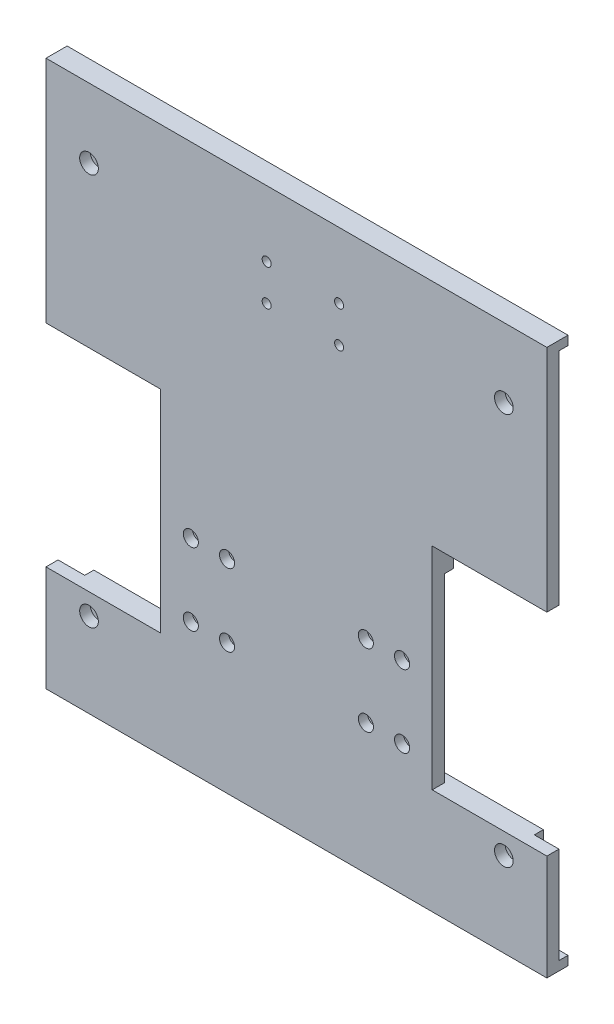
SolidWorks part; units mm, degrees
material "純碳鋼"
ref_plane "前基準面" through (0, 0, 0) normal (0, 0, 1) x (1, 0, 0)
ref_plane "上基準面" through (0, 0, 0) normal (0, 1, 0) x (1, 0, 0)
ref_plane "右基準面" through (0, 0, 0) normal (1, 0, 0) x (0, 0, -1)
sketch "草圖1" plane through (0, 0, 0) normal (0, 0, 1) x (1, 0, 0)
  line L1 (75, -80) -> (-75, -80)
  line L2 (75, -80) -> (75, 80)
  line L3 (75, 80) -> (-75, 80)
  line L4 (-75, -80) -> (-75, 80)
  line L5 (75, -80) -> (-75, 80) construction
  line L6 (75, 80) -> (-75, -80) construction
  point P0 (0, 0)
  dimension "D1" = 150
  dimension "D2" = 160
extrude "填料-伸長1" add sketch "草圖1" along normal blind 7
sketch "草圖2" plane through (0, 0, 0) normal (0, 0, -1) x (-1, 0, 0)
  line L0 (-45, 80) -> (-45, -80)
  line L1 (-75, 80) -> (75, 80) construction
  line L2 (75, -80) -> (-75, -80) construction
  line L3 (45, 80) -> (45, -80)
  line L4 (-75, -80) -> (-75, 80) construction
  line L6 (-45, 35) -> (45, 35)
  line L7 (-75, 12) -> (-45, 12)
  line L8 (-45, 12) -> (-45, -58)
  line L9 (-45, -58) -> (-75, -58)
  line L10 (-75, -58) -> (-75, 12)
  line L11 (45, 12) -> (75, 12)
  line L12 (75, 80) -> (75, -80) construction
  line L13 (75, 12) -> (75, -58)
  line L14 (75, -58) -> (45, -58)
  line L15 (45, -58) -> (45, 12)
  dimension "D1" = 90
  dimension "D2" = 30
  dimension "D3" = 45
  dimension "D4" = 70
  dimension "D5" = 70
  dimension "D6" = 22
extrude "除料-伸長1" cut sketch "草圖2" against normal blind 10 contours L13 L14 L15 L11 | L10 L7 L8 L9
sketch "草圖3" plane through (0, 0, 0) normal (0, 0, -1) x (-1, 0, 0)
  line L0 (-45, -58) -> (45, -58)
  line L1 (-45, 12) -> (-45, -58) construction
  line L2 (-45, -57) -> (-11, -57)
  line L3 (-11, -57) -> (-11, -10.5)
  line L4 (-11, -10.5) -> (-45, -10.5)
  circle A0 centre (-35, -25.75) radius 1.5
  circle A1 centre (-23, -25.75) radius 1.5
  circle A2 centre (-35.025, -49.75) radius 1.5
  circle A3 centre (-23.025, -49.75) radius 1.5
  dimension "D3" = 10
  dimension "D5" = 12
  dimension "D7" = 24
  dimension "D9" = 12
  dimension "D1" = 34
  dimension "D2" = 46.5
  dimension "D4" = 24
  dimension "D6" = 15.25
  dimension "D8" = 7.25
  dimension "D10" = 1
extrude "除料-伸長2" cut sketch "草圖3" against normal blind 10 contours A0 | A1 | A2 | A3
sketch "草圖4" plane through (0, 0, 0) normal (0, 0, -1) x (-1, 0, 0)
  line L0 (45, -57) -> (11, -57)
  line L1 (11, -57) -> (11, -10.5)
  line L2 (11, -10.5) -> (45, -10.5)
  line L3 (45, -58) -> (45, 12) construction
  line L4 (-45, -58) -> (45, -58)
  circle A0 centre (35, -25.75) radius 1.5
  circle A1 centre (23, -25.75) radius 1.5
  circle A2 centre (35, -49.75) radius 1.5
  circle A3 centre (23, -49.75) radius 1.5
  dimension "D3" = 10
  dimension "D5" = 12
  dimension "D6" = 24
  dimension "D8" = 12
  dimension "D1" = 34
  dimension "D2" = 46.5
  dimension "D4" = 1
  dimension "D7" = 15.25
  dimension "D9" = 24
  dimension "D10" = 15.25
extrude "除料-伸長3" cut sketch "草圖4" against normal blind 10 contours A1 | A0 | A2 | A3
sketch "草圖5" plane through (0, 0, 7) normal (0, 0, 1) x (1, 0, 0)
  circle A0 centre (-35, -25.75) radius 2.5
  circle A1 centre (-23, -25.75) radius 2.5
  circle A2 centre (-35, -49.75) radius 2.5
  circle A3 centre (-23, -49.75) radius 2.5
  circle A4 centre (23.025, -49.75) radius 2.5
  circle A5 centre (35.025, -49.75) radius 2.5
  circle A6 centre (35, -25.75) radius 2.5
  circle A7 centre (23, -25.75) radius 2.5
extrude "除料-伸長4" cut sketch "草圖5" against normal blind 3
sketch "草圖6" plane through (0, 0, 0) normal (0, 0, -1) x (-1, 0, 0)
  line L1 (-14.135, 54.1775) -> (9.865, 54.1775)
  line L2 (-14.135, 54.1775) -> (-14.135, 66.1775)
  line L3 (-14.135, 66.1775) -> (9.865, 66.1775)
  line L4 (9.865, 54.1775) -> (9.865, 66.1775)
  line L5 (-14.135, 54.1775) -> (9.865, 66.1775) construction
  line L6 (-14.135, 66.1775) -> (9.865, 54.1775) construction
  circle A0 centre (-14.135, 66.1775) radius 1.5
  circle A1 centre (9.865, 66.1775) radius 1.5
  circle A2 centre (9.865, 54.1775) radius 1.5
  circle A3 centre (-14.135, 54.1775) radius 1.5
  point P0 (-2.135, 60.1775)
  dimension "D1" = 12
  dimension "D2" = 24
extrude "除料-伸長5" cut sketch "草圖6" against normal blind 10 contours A0 | A3 | A2 | A1
sketch "草圖7" plane through (0, 0, 0) normal (0, 0, -1) x (-1, 0, 0)
  line L0 (-75, 70) -> (75, 70)
  line L1 (-75, 12) -> (-75, 80) construction
  line L2 (75, 80) -> (75, 12) construction
  line L3 (-75, -70) -> (75, -70)
  line L4 (-75, -80) -> (-75, -58) construction
  line L5 (75, -58) -> (75, -80) construction
  line L6 (-62.5, 80) -> (-62.5, -80)
  line L7 (-75, 80) -> (75, 80) construction
  line L8 (75, -80) -> (-75, -80) construction
  line L9 (62.5, 80) -> (62.5, -80)
  line L10 (-75, -60) -> (75, -60)
  line L11 (-75, 60) -> (75, 60)
  line L12 (-75, -60) -> (-62.5, -70)
  line L13 (-75, -70) -> (-62.5, -60)
  line L14 (-75, 70) -> (-62.5, 60)
  line L15 (-75, 60) -> (-62.5, 70)
  line L16 (75, 60) -> (62.5, 70)
  line L17 (62.5, 60) -> (75, 70)
  line L18 (75, -60) -> (62.5, -70)
  line L19 (62.5, -60) -> (75, -70)
  line L21 (72.33, -65) -> (70.54, -61.8996)
  line L22 (70.54, -61.8996) -> (66.96, -61.8996)
  line L23 (66.96, -61.8996) -> (65.17, -65)
  line L24 (65.17, -65) -> (66.96, -68.1004)
  line L25 (66.96, -68.1004) -> (70.54, -68.1004)
  line L26 (70.54, -68.1004) -> (72.33, -65)
  line L27 (72.33, 65) -> (70.54, 68.1004)
  line L28 (70.54, 68.1004) -> (66.96, 68.1004)
  line L29 (66.96, 68.1004) -> (65.17, 65)
  line L30 (65.17, 65) -> (66.96, 61.8996)
  line L31 (66.96, 61.8996) -> (70.54, 61.8996)
  line L32 (70.54, 61.8996) -> (72.33, 65)
  line L33 (-65.17, 65) -> (-66.96, 68.1004)
  line L34 (-66.96, 68.1004) -> (-70.54, 68.1004)
  line L35 (-70.54, 68.1004) -> (-72.33, 65)
  line L36 (-72.33, 65) -> (-70.54, 61.8996)
  line L37 (-70.54, 61.8996) -> (-66.96, 61.8996)
  line L38 (-66.96, 61.8996) -> (-65.17, 65)
  line L39 (-65.17, -65) -> (-66.96, -61.8996)
  line L40 (-66.96, -61.8996) -> (-70.54, -61.8996)
  line L41 (-70.54, -61.8996) -> (-72.33, -65)
  line L42 (-72.33, -65) -> (-70.54, -68.1004)
  line L43 (-70.54, -68.1004) -> (-66.96, -68.1004)
  line L44 (-66.96, -68.1004) -> (-65.17, -65)
  circle A0 centre (68.75, -65) radius 3.1004 construction
  circle A1 centre (68.75, 65) radius 3.1004 construction
  circle A2 centre (-68.75, 65) radius 3.1004 construction
  circle A3 centre (-68.75, -65) radius 3.1004 construction
  dimension "D1" = 10
  dimension "D2" = 10
  dimension "D3" = 12.5
  dimension "D4" = 12.5
  dimension "D5" = 10
  dimension "D6" = 10
  dimension "D7" = 3.58
  dimension "D8" = 3.58
  dimension "D9" = 3.58
  dimension "D10" = 3.58
extrude "除料-伸長6" cut sketch "草圖7" against normal blind 0.5 contours L33 L34 L35 L36 L37 L38 | L27 L28 L29 L30 L31 L32 | L24 L25 L26 L21 L22 L23 | L41 L42 L43 L44 L39 L40
sketch "草圖8" plane through (0, 0, 0.5) normal (0, 0, -1) x (-1, 0, 0)
  line L0 (-70.54, 68.1004) -> (-66.96, 61.8996) construction
  line L1 (66.96, 68.1004) -> (70.54, 61.8996) construction
  line L2 (-65.75, 65) -> (-67.25, 67.5981)
  line L3 (-67.25, 67.5981) -> (-70.25, 67.5981)
  line L4 (-70.25, 67.5981) -> (-71.75, 65)
  line L5 (-71.75, 65) -> (-70.25, 62.4019)
  line L6 (-70.25, 62.4019) -> (-67.25, 62.4019)
  line L7 (-67.25, 62.4019) -> (-65.75, 65)
  line L8 (-70.54, -61.8996) -> (-66.96, -68.1004) construction
  line L9 (71.75, 65) -> (70.25, 67.5981)
  line L10 (70.25, 67.5981) -> (67.25, 67.5981)
  line L11 (67.25, 67.5981) -> (65.75, 65)
  line L12 (65.75, 65) -> (67.25, 62.4019)
  line L13 (67.25, 62.4019) -> (70.25, 62.4019)
  line L14 (70.25, 62.4019) -> (71.75, 65)
  line L15 (66.96, -61.8996) -> (70.54, -68.1004) construction
  line L16 (-65.75, -65) -> (-67.25, -62.4019)
  line L17 (-67.25, -62.4019) -> (-70.25, -62.4019)
  line L18 (-70.25, -62.4019) -> (-71.75, -65)
  line L19 (-71.75, -65) -> (-70.25, -67.5981)
  line L20 (-70.25, -67.5981) -> (-67.25, -67.5981)
  line L21 (-67.25, -67.5981) -> (-65.75, -65)
  line L23 (71.75, -65) -> (70.25, -62.4019)
  line L24 (70.25, -62.4019) -> (67.25, -62.4019)
  line L25 (67.25, -62.4019) -> (65.75, -65)
  line L26 (65.75, -65) -> (67.25, -67.5981)
  line L27 (67.25, -67.5981) -> (70.25, -67.5981)
  line L28 (70.25, -67.5981) -> (71.75, -65)
  circle A0 centre (-68.75, 65) radius 2.5981 construction
  circle A1 centre (68.75, 65) radius 2.5981 construction
  circle A2 centre (-68.75, -65) radius 2.5981 construction
  circle A3 centre (68.75, -65) radius 2.5981 construction
  dimension "D1" = 3
  dimension "D2" = 3
  dimension "D3" = 3
  dimension "D4" = 3
sketch "草圖10" plane through (0, 0, 0) normal (0, 0, -1) x (-1, 0, 0)
  line L6 (0, 80) -> (0, 70) construction
  line L7 (-75, 80) -> (75, 80) construction
  line L10 (-35, 72.6896) -> (35, 72.6896)
  line L11 (-35, 72.6896) -> (-35, 69.6896)
  line L12 (-35, 69.6896) -> (35, 69.6896)
  line L13 (35, 72.6896) -> (35, 69.6896)
  point P9 (0, 72.6896)
  dimension "D1" = 3
  dimension "D2" = 70
extrude "填料-伸長2" add sketch "草圖10" along normal blind 10 contours L12 L13 L10 L11
sketch "草圖11" plane through (0, 0, 0) normal (0, 0, -1) x (-1, 0, 0)
  line L0 (-35, 12) -> (35, 12)
  line L1 (45, 2) -> (45, -58)
  line L2 (45, -58) -> (-45, -58)
  line L3 (-45, -58) -> (-45, 2)
  line L4 (-45, 12) -> (-45, -58) construction
  arc A0 (35, 12) -> (45, 2) centre (35, 2) cw
  arc A1 (-35, 12) -> (-45, 2) centre (-35, 2) ccw
  point P10 (45, 12)
  point P13 (-45, 12)
  dimension "D1" = 10
extrude "除料-伸長11" cut sketch "草圖11" against normal blind 3 contours L3 A1 L0 A0 L1 L2
sketch "草圖13" plane through (0, -80, 0) normal (0, -1, 0) x (1, 0, 0)
  line L1 (-75, 7) -> (75, 7)
  line L2 (-75, 7) -> (-75, 0)
  line L3 (-75, 0) -> (75, 0)
  line L4 (75, 7) -> (75, 0)
extrude "填料-伸長4" add sketch "草圖13" along normal blind 13
sketch "草圖14" plane through (0, 0, 0) normal (0, 0, -1) x (-1, 0, 0)
  line L1 (-35, 12) -> (-60, 12)
  line L2 (-35, 12) -> (-35, 17)
  line L3 (-35, 17) -> (-60, 17)
  line L4 (-60, 12) -> (-60, 17)
  line L5 (35, 12) -> (60, 12)
  line L6 (35, 12) -> (35, 17)
  line L7 (35, 17) -> (60, 17)
  line L8 (60, 12) -> (60, 17)
  dimension "D1" = 25
  dimension "D2" = 5
  dimension "D3" = 5
  dimension "D4" = 25
extrude "填料-伸長5" add sketch "草圖14" along normal blind 10
sketch "草圖17" plane through (0, 80, 0) normal (0, 1, 0) x (1, 0, 0)
  line L1 (-75, 0) -> (75, 0)
  line L2 (-75, 0) -> (-75, -7)
  line L3 (-75, -7) -> (75, -7)
  line L4 (75, 0) -> (75, -7)
extrude "填料-伸長6" add sketch "草圖17" along normal blind 8
sketch "草圖19" plane through (75, 0, 0) normal (1, 0, 0) x (0, 0, -1)
  line L1 (-7, 88) -> (0, 88)
  line L2 (-7, 88) -> (-7, 12)
  line L3 (-7, 12) -> (0, 12)
  line L4 (0, 88) -> (0, 12)
extrude "填料-伸長8" add sketch "草圖19" along normal blind 8
sketch "草圖20" plane through (-75, 0, 0) normal (-1, 0, 0) x (0, 0, 1)
  line L1 (0, 88) -> (7, 88)
  line L2 (0, 88) -> (0, 12)
  line L3 (0, 12) -> (7, 12)
  line L4 (7, 88) -> (7, 12)
extrude "填料-伸長9" add sketch "草圖20" along normal blind 8
sketch "草圖22" plane through (0, 0, 0) normal (0, 0, -1) x (-1, 0, 0)
  line L1 (-83, 12) -> (-73, 12)
  line L2 (-83, 12) -> (-83, 17)
  line L3 (-83, 17) -> (-73, 17)
  line L4 (-73, 12) -> (-73, 17)
  line L5 (83, 12) -> (73, 12)
  line L6 (83, 12) -> (83, 17)
  line L7 (83, 17) -> (73, 17)
  line L8 (73, 12) -> (73, 17)
  dimension "D1" = 10
  dimension "D2" = 5
  dimension "D3" = 10
  dimension "D4" = 5
extrude "填料-伸長10" [suppressed] add sketch "草圖22" along normal blind 20
sketch "草圖23" [suppressed] plane through (0, 17, 0) normal (0, 1, 0) x (1, 0, 0)
  line L0 (80, 20) -> (80, 0) construction
  line L1 (75, 20) -> (85, 20) construction
  line L2 (75, 0) -> (85, 0) construction
  line L3 (80, 20) -> (85, 20) construction
  line L4 (85, 20) -> (82.5, 20) construction
  line L5 (82.5, 20) -> (82.5, 0) construction
  line L6 (85, 0) -> (-85, 0) construction
  line L7 (80, 10) -> (85, 10) construction
  line L8 (81.25, 19.5) -> (83.75, 19.5)
  line L9 (81.25, 19.5) -> (81.25, 11)
  line L10 (81.25, 11) -> (83.75, 11)
  line L11 (83.75, 19.5) -> (83.75, 11)
  line L12 (85, 20) -> (85, 0) construction
  line L14 (76.25, 0) -> (78.75, 0)
  line L15 (76.25, 0) -> (76.25, 8.5)
  line L16 (76.25, 8.5) -> (78.75, 8.5)
  line L17 (78.75, 0) -> (78.75, 8.5)
  point P20 (82.5, 19.5)
  dimension "D1" = 2.5
  dimension "D2" = 0.5
  dimension "D3" = 8.5
  dimension "D4" = 8.5
extrude "填料-伸長11" [suppressed] add sketch "草圖23" along normal blind 15
sketch "草圖24" [suppressed] plane through (0, 17, 0) normal (0, 1, 0) x (1, 0, 0)
  line L0 (-85, 20) -> (-75, 20) construction
  line L1 (-75, 20) -> (-80, 20) construction
  line L2 (-80, 20) -> (-80, 0) construction
  line L3 (-85, 0) -> (-75, 0) construction
  line L4 (-85, 10) -> (-75, 10)
  line L5 (-83.75, 19.5) -> (-81.25, 19.5)
  line L6 (-83.75, 19.5) -> (-83.75, 11)
  line L7 (-83.75, 11) -> (-81.25, 11)
  line L8 (-81.25, 19.5) -> (-81.25, 11)
  line L9 (-85, 20) -> (-85, 0) construction
  line L10 (-75, 20) -> (-75, 0) construction
  line L11 (85, 0) -> (-85, 0) construction
  line L12 (-78.8099, 0) -> (-86.1901, 0)
  line L13 (-78.8099, 0) -> (-78.8099, 8.5)
  line L14 (-78.8099, 8.5) -> (-86.1901, 8.5)
  line L15 (-86.1901, 0) -> (-86.1901, 8.5)
  line L16 (-80, 20) -> (-85, 20) construction
  line L17 (-85, 20) -> (-82.5, 20) construction
  line L18 (-82.5, 20) -> (-82.5, 0) construction
  point P18 (-82.5, 19.5)
  point P25 (-82.5, 8.5)
  line M7 (-85, 0) -> (-75, 0)
  dimension "D1" = 2.5
  dimension "D2" = 8.5
  dimension "D3" = 0.5
  dimension "D4" = 8.5
extrude "填料-伸長12" [suppressed] add sketch "草圖24" along normal blind 15 contours L8 L5 L6 L7 | L15 L14 L13 M7
sketch "草圖25" plane through (0, 0, 0) normal (0, 0, -1) x (-1, 0, 0)
  line L0 (0, 88) -> (0, 72.6896) construction
  line L1 (-83, 88) -> (83, 88) construction
  line L2 (-35, 72.6896) -> (35, 72.6896) construction
  line L4 (-35, 86.75) -> (35, 86.75)
  line L5 (-35, 86.75) -> (-35, 84.25)
  line L6 (-35, 84.25) -> (35, 84.25)
  line L7 (35, 86.75) -> (35, 84.25)
  dimension "D1" = 1.25
  dimension "D2" = 2.5
  dimension "D3" = 70
extrude "填料-伸長13" [suppressed] add sketch "草圖25" along normal blind 3
sketch "草圖26" plane through (0, 0, 0) normal (0, 0, -1) x (-1, 0, 0)
  line L0 (-83, 12) -> (-74.5, 12)
  line L1 (-83, 12) -> (-60, 12) construction
  line L4 (74.5, 12) -> (83, 12)
  line L5 (60, 12) -> (83, 12) construction
  line L6 (-83, 88) -> (83, 88) construction
  line L7 (-83, 12) -> (-83, 88) construction
  line L8 (83, 88) -> (83, 12) construction
  line L11 (-83, 12) -> (-74.5, 12)
  line L12 (-74.5, 79.5) -> (74.5, 79.5)
  line L13 (74.5, 79.5) -> (74.5, 12)
  line L14 (-74.5, 79.5) -> (-74.5, 12)
  line L15 (-83, 12) -> (-83, 85)
  line L16 (-83, 85) -> (83, 85)
  line L17 (83, 12) -> (83, 85)
  line M32 (60, 12) -> (83, 12)
  line M36 (-83, 12) -> (-60, 12)
  dimension "D1" = 149
  dimension "D2" = 5.5
  dimension "D6" = 3
extrude "除料-伸長14" cut sketch "草圖26" against normal blind 3 contours L17 L16 L15 L14 L12 L13 M32 M36
sketch "草圖27" plane through (75, 0, 0) normal (1, 0, 0) x (0, 0, -1)
  line L1 (-7, -58) -> (0, -58)
  line L2 (-7, -58) -> (-7, -93)
  line L3 (-7, -93) -> (0, -93)
  line L4 (0, -58) -> (0, -93)
extrude "填料-伸長14" add sketch "草圖27" along normal blind 8
sketch "草圖28" plane through (-75, 0, 0) normal (-1, 0, 0) x (0, 0, 1)
  line L1 (0, -58) -> (7, -58)
  line L2 (0, -58) -> (0, -93)
  line L3 (0, -93) -> (7, -93)
  line L4 (7, -58) -> (7, -93)
extrude "填料-伸長15" add sketch "草圖28" along normal blind 8
sketch "草圖29" plane through (0, 0, 0) normal (0, 0, -1) x (-1, 0, 0)
  line L0 (-83, -93) -> (-83, -58) construction
  line L1 (83, -58) -> (-83, -58) construction
  line L2 (83, -58) -> (83, -93) construction
  line L11 (83, -58) -> (83, -90)
  line L12 (83, -90) -> (-83, -90)
  line L13 (-83, -90) -> (-83, -58)
  line L14 (-83, -58) -> (-74.8414, -58)
  line L15 (-74.8414, -58) -> (-74.8414, -84.5)
  line L16 (-74.8414, -84.5) -> (74.1586, -84.5)
  line L17 (74.1586, -84.5) -> (74.1586, -58)
  line L18 (74.1586, -58) -> (83, -58)
  dimension "D2" = 5.5
  dimension "D4" = 149
extrude "除料-伸長15" cut sketch "草圖29" against normal blind 3
extrude "除料-伸長16" cut sketch "草圖8" against normal blind 2
sketch "草圖30" plane through (0, 0, 0) normal (0, 0, 1) x (1, 0, 0)
  line L0 (70.54, 68.1004) -> (66.96, 61.8996) construction
  line L1 (70.54, -61.8996) -> (66.96, -68.1004) construction
  line L2 (0, -93) -> (0, 88) construction
  line L3 (-83, -93) -> (83, -93) construction
  line L4 (83, 88) -> (-83, 88) construction
  circle A0 centre (68.75, -65) radius 1.6
  circle A1 centre (68.75, 65) radius 1.6
  circle A2 centre (-68.75, -65) radius 1.6
  circle A3 centre (-68.75, 65) radius 1.6
extrude "除料-伸長17" cut sketch "草圖30" along normal blind 7
sketch "草圖31" plane through (0, 0, 7) normal (0, 0, 1) x (1, 0, 0)
  circle A0 centre (-68.75, 65) radius 3.1
  circle A1 centre (-68.75, -65) radius 3.1
  circle A2 centre (68.75, -65) radius 3.1
  circle A3 centre (68.75, 65) radius 3.1
extrude "除料-伸長18" cut sketch "草圖31" against normal blind 3.5
sketch "草圖32" plane through (0, 0, 0) normal (0, 0, -1) x (-1, 0, 0)
  circle A0 centre (-14.135, 66.1775) radius 2.5
  circle A1 centre (-14.135, 54.1775) radius 2.5
  circle A2 centre (9.865, 54.1775) radius 2.5
  circle A3 centre (9.865, 66.1775) radius 2.5
extrude "除料-伸長19" cut sketch "草圖32" against normal blind 4
sketch "草圖33" plane through (0, 0, 7) normal (0, 0, 1) x (1, 0, 0)
  line L0 (-9.865, 88) -> (-9.865, 66.1775) construction
  line L2 (-83, 88) -> (83, 88) construction
  line L3 (-9.865, 66.1775) -> (-16.865, 66.1775)
  line L4 (-16.865, 66.1775) -> (-16.865, 71.1775) construction
  line L5 (14.135, 54.1775) -> (21.135, 54.1775) construction
  line L6 (21.135, 54.1775) -> (21.135, 49.1775) construction
  line L7 (-9.865, 66.1775) -> (-9.865, 54.1775)
  line L8 (-16.865, 71.1775) -> (21.135, 71.1775)
  line L9 (-16.865, 71.1775) -> (-16.865, 49.1775)
  line L10 (-16.865, 49.1775) -> (21.135, 49.1775)
  line L11 (21.135, 71.1775) -> (21.135, 49.1775)
  line L12 (14.135, 54.1775) -> (-9.865, 54.1775)
  dimension "D1" = 22
  dimension "D2" = 38
  dimension "D3" = 5
  dimension "D4" = 7
  dimension "D5" = 12
  dimension "D6" = 24
